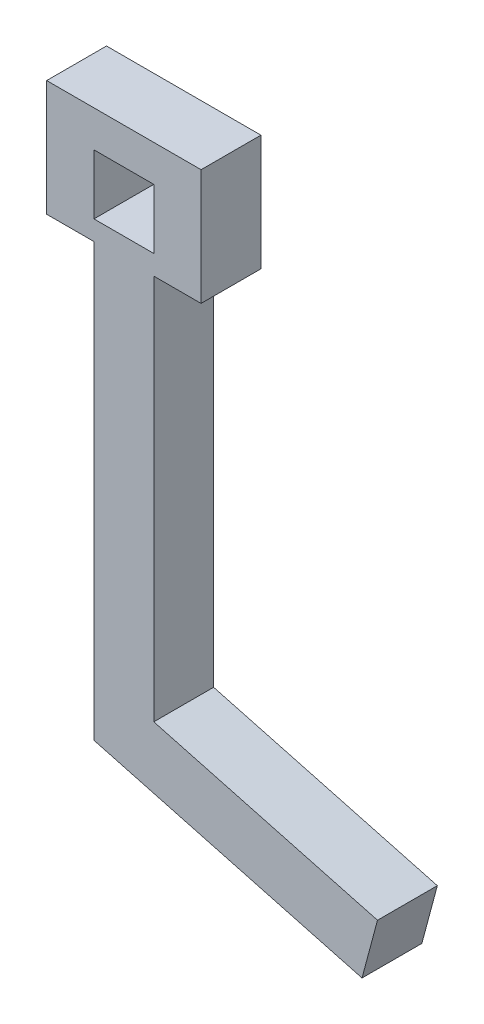
SolidWorks part; units mm, degrees
ref_plane "前视基准面" through (0, 0, 0) normal (0, 0, 1) x (1, 0, 0)
ref_plane "上视基准面" through (0, 0, 0) normal (0, 1, 0) x (1, 0, 0)
ref_plane "右视基准面" through (0, 0, 0) normal (1, 0, 0) x (0, 0, -1)
sketch "草图1" plane through (0, 0, 0) normal (0, 0, 1) x (1, 0, 0)
  line L1 (28.4667, -18.9173) -> (28.4667, 92.9763)
  line L2 (28.4667, 92.9763) -> (16.2167, 92.9763)
  line L3 (16.2167, 92.9763) -> (16.2167, 122.9763)
  line L4 (16.2167, 122.9763) -> (56.2167, 122.9763)
  line L5 (56.2167, 122.9763) -> (56.2167, 92.9763)
  line L6 (56.2167, 92.9763) -> (43.9667, 92.9763)
  line L7 (43.9667, 92.9763) -> (43.9667, -7.0237)
  line L8 (43.9667, 98.0583) -> (28.4667, 98.0583)
  line L9 (28.4667, 98.0583) -> (28.4667, 113.5583)
  line L10 (28.4667, 113.5583) -> (43.9667, 113.5583)
  line L11 (43.9667, 113.5583) -> (43.9667, 98.0583)
  line L12 (36.2167, 113.5583) -> (36.2167, -20.9939) construction
  line L13 (43.9667, -7.0237) -> (101.9222, -22.5528)
  line L14 (101.9222, -22.5528) -> (97.9105, -37.5247)
  line L15 (97.9105, -37.5247) -> (28.4667, -18.9173)
  dimension "D1" = 15.5
  dimension "D2" = 15.5
  dimension "D3" = 15.5
  dimension "D4" = 15.5
  dimension "D5" = 40
  dimension "D6" = 30
  dimension "D7" = 12.25
  dimension "D8" = 9.418
  dimension "D9" = 100
  dimension "D10" = 60
  dimension "D11" = 105
extrude "凸台-拉伸1" add sketch "草图1" along normal blind 15.5
